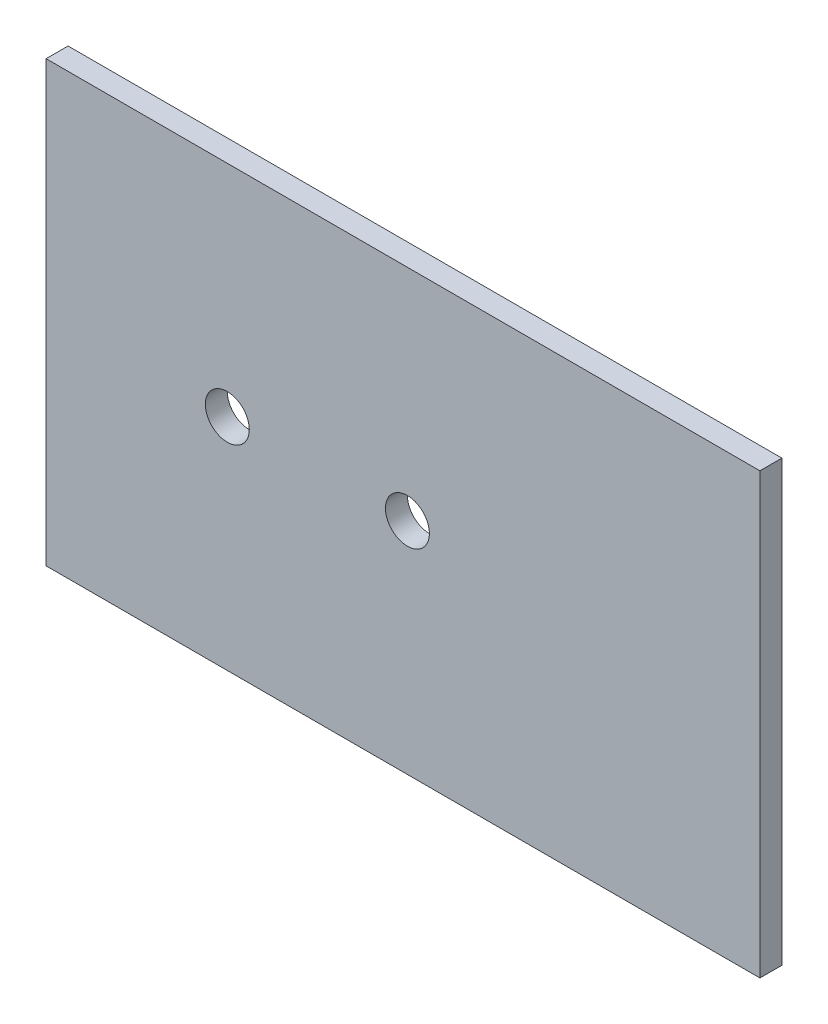
SolidWorks part; units mm, degrees
ref_plane "Plano frontal" through (0, 0, 0) normal (0, 0, 1) x (1, 0, 0)
ref_plane "Plano superior" through (0, 0, 0) normal (0, 1, 0) x (1, 0, 0)
ref_plane "Plano direito" through (0, 0, 0) normal (1, 0, 0) x (0, 0, -1)
sketch "Esboço1" plane through (0, 0, 0) normal (0, 0, 1) x (1, 0, 0)
  line L1 (-35.3819, 37.5094) -> (29.6181, 37.5094)
  line L2 (-35.3819, 37.5094) -> (-35.3819, -2.4906)
  line L3 (-35.3819, -2.4906) -> (29.6181, -2.4906)
  line L4 (29.6181, 37.5094) -> (29.6181, -2.4906)
  dimension "D1" = 65
  dimension "D2" = 40
extrude "Ressalto-extrusão1" add sketch "Esboço1" along normal blind 2
sketch "Esboço2" plane through (0, 0, 2) normal (0, 0, 1) x (1, 0, 0)
  line L0 (-35.3819, 37.5094) -> (-35.3819, -2.4906) construction
  line L1 (-35.3819, -2.4906) -> (29.6181, -2.4906) construction
  circle A0 centre (-18.8819, 17.5094) radius 2
  circle A1 centre (-2.4819, 17.5094) radius 2
  dimension "D1" = 4
  dimension "D2" = 4
  dimension "D3" = 16.4
  dimension "D4" = 16.5
  dimension "D5" = 20
  dimension "D6" = 20
extrude "Corte-extrusão1" cut sketch "Esboço2" against normal through all
